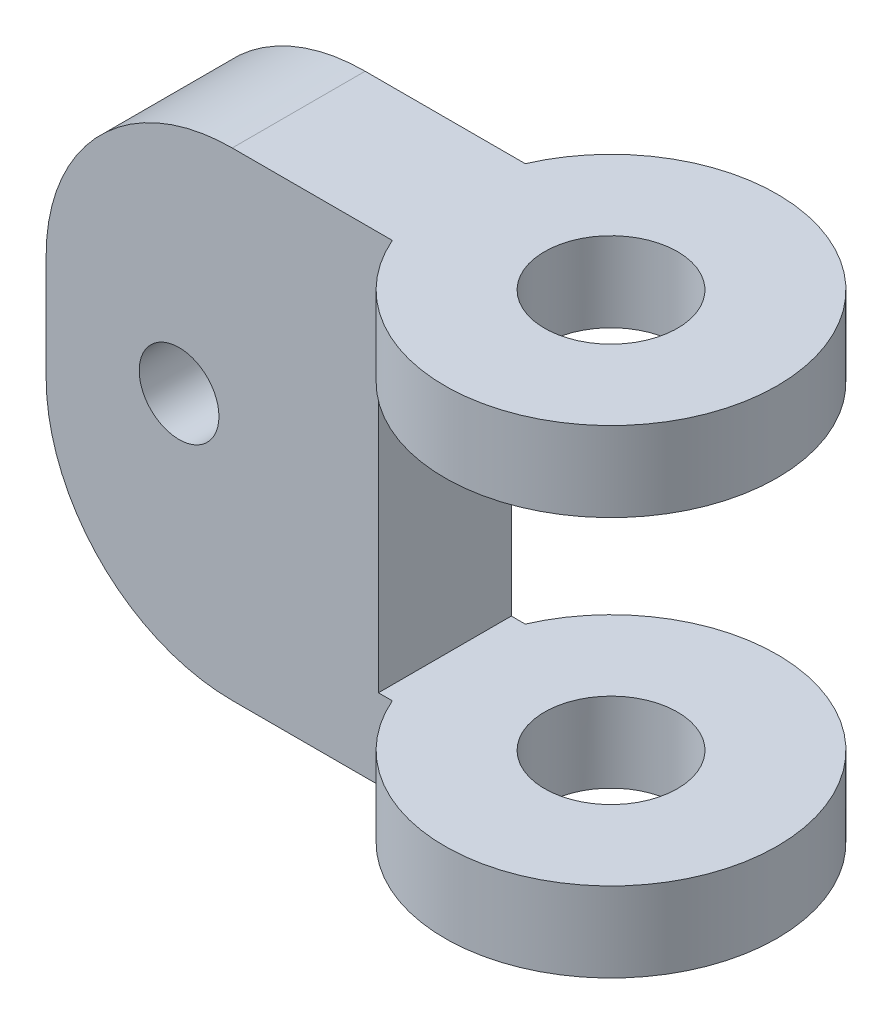
SolidWorks part; units mm, degrees
ref_plane "Alzado" through (0, 0, 0) normal (0, 0, 1) x (1, 0, 0)
ref_plane "Planta" through (0, 0, 0) normal (0, 1, 0) x (1, 0, 0)
ref_plane "Vista lateral" through (0, 0, 0) normal (1, 0, 0) x (0, 0, -1)
sketch "Croquis1" plane through (0, 0, 0) normal (0, 0, 1) x (1, 0, 0)
  line L0 (11.25, 14.1) -> (11.25, 11.1)
  line L1 (5.75, -0.9) -> (11.25, -0.9)
  line L2 (-1.25, 6.1) -> (-1.25, 10.1)
  line L3 (5.75, 17.1) -> (11.25, 17.1)
  line L4 (11.25, 11.1) -> (23.75, 11.1) construction
  line L5 (-1.25, -0.9) -> (1.25, 0.9) construction
  line L6 (-1.25, 17.1) -> (-1.0254, 14.0276) construction
  line L7 (11.25, 11.1) -> (11.25, 5.1)
  line L8 (-1.25, 8.1) -> (23.75, 8.1) construction
  line L9 (23.75, -0.9) -> (23.75, 2.1)
  line L10 (11.25, 5.1) -> (11.25, 2.1)
  line L11 (23.75, 11.1) -> (23.75, 14.1) construction
  line L12 (23.75, 14.1) -> (11.25, 14.1)
  line L13 (11.25, 17.1) -> (-1.25, 17.1) construction
  line L14 (11.25, -0.9) -> (23.75, -0.9)
  line L15 (23.75, 2.1) -> (11.25, 2.1)
  line L16 (11.25, 17.1) -> (23.75, 17.1)
  line L17 (23.75, 17.1) -> (23.75, 14.1)
  circle A0 centre (3.75, 8.1) radius 1.5
  arc A1 (-1.25, 10.1) -> (5.75, 17.1) centre (5.75, 10.1) cw
  arc A2 (5.75, -0.9) -> (-1.25, 6.1) centre (5.75, 6.1) cw
  point P0 (0, 0)
  dimension "D6" = 3
  dimension "D4" = 7
  dimension "D2" = 18
  dimension "D3" = 12.5
  dimension "D7" = 5
  dimension "D8" = 9
  dimension "D10" = 3
  dimension "D11" = 3
extrude "Saliente-Extruir1" add sketch "Croquis1" along normal blind 15
sketch "Croquis2" plane through (0, 0, 0) normal (0, 1, 0) x (1, 0, 0)
  line L3 (17.5, -1.25) -> (11.25, 0)
  line L4 (17.5, -13.75) -> (11.25, -15)
  line L5 (11.25, -15) -> (11.25, -17.9613)
  line L6 (11.25, -17.9613) -> (29.6635, -17.9613)
  line L7 (29.6635, -17.9613) -> (29.6635, 1.8686)
  line L8 (29.6635, 1.8686) -> (11.1263, 1.8686)
  line L9 (11.1263, 1.8686) -> (11.25, 0)
  circle A0 centre (17.5, -7.5) radius 2.5
  arc A1 (17.5, -13.75) -> (17.5, -1.25) centre (17.5, -7.5) ccw
  dimension "D1" = 5
extrude "Cortar-Extruir1" cut sketch "Croquis2" along normal mid plane 40
sketch "Croquis3" plane through (0, 17.1, 0) normal (0, 1, 0) x (1, 0, 0)
  line L0 (-1.25, -15) -> (-1.25, 0) construction
  line L1 (-2.0507, -10) -> (11.7718, -10)
  line L2 (-9.9732, -8.842) -> (-9.9732, -6.158)
  line L3 (-2.0507, -5) -> (11.7718, -5)
  line L4 (17.5, -1.25) -> (17.5, 1.6133)
  line L5 (-9.9732, -8.842) -> (15, -5) construction
  line L6 (-9.9732, -6.158) -> (15, -10) construction
  line L7 (17.5, -1.25) -> (17.5, -13.75) construction
  line L10 (17.5, 1.6133) -> (-2.0507, 1.6133)
  line L11 (-2.0507, 1.6133) -> (-2.0507, -5)
  line L12 (-2.0507, -10) -> (-2.3251, -18.2596)
  line L13 (-2.3251, -18.2596) -> (20.8404, -18.2596)
  line L14 (20.8404, -18.2596) -> (17.5, -13.75)
  line L15 (5.25, 0) -> (2.25, 0) construction
  arc A2 (17.5, -1.25) -> (17.5, -13.75) centre (17.5, -7.5) ccw
  point P0 (-1.25, -7.5)
  point P12 (3.75, 0)
  dimension "D1" = 5
  dimension "D2" = 25
  dimension "D3" = 5
extrude "Cortar-Extruir2" cut sketch "Croquis3" against normal blind 22
ref_plane "Plano1" through (0, 0, 7.5) normal (0, 0, 1) x (1, 0, 0)
